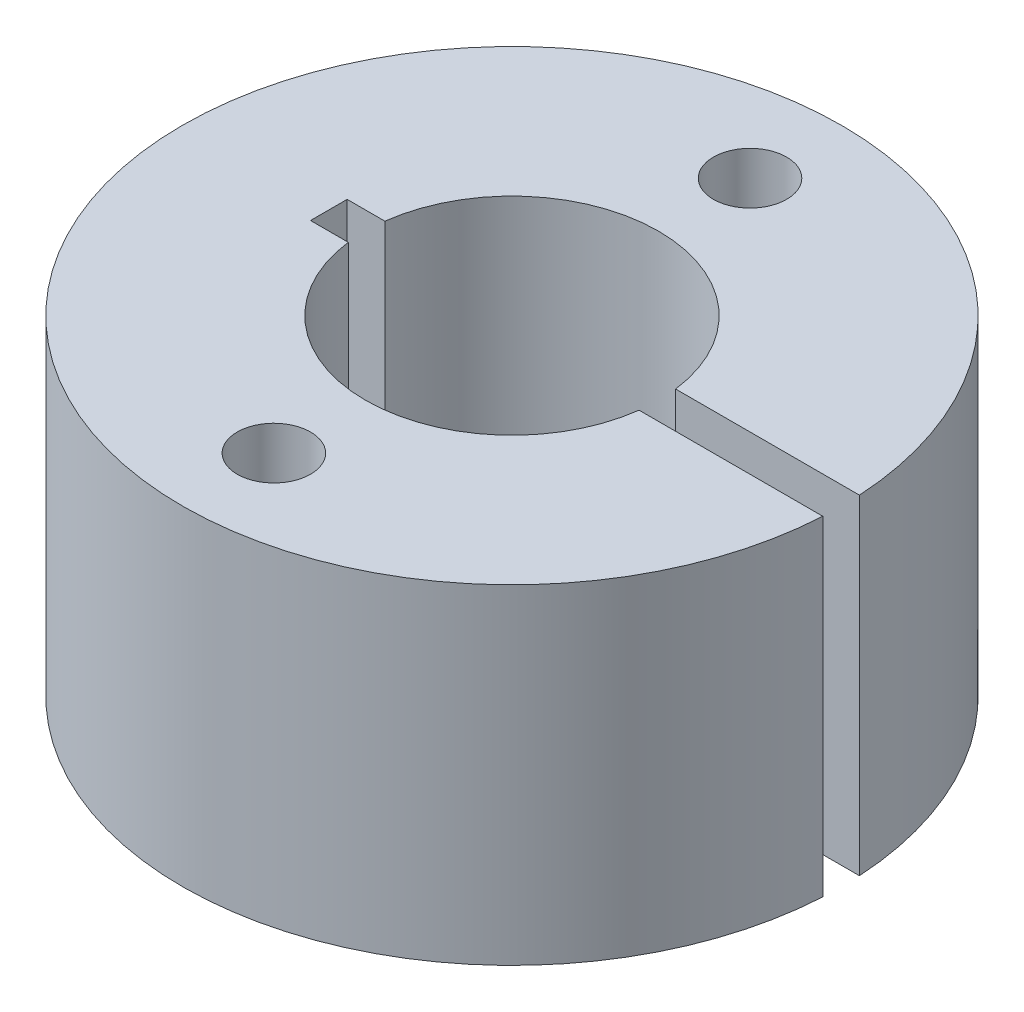
SolidWorks part; units mm, degrees
ref_plane "Plan de face" through (0, 0, 0) normal (0, 0, 1) x (1, 0, 0)
ref_plane "Plan de dessus" through (0, 0, 0) normal (0, 1, 0) x (1, 0, 0)
ref_plane "Plan de droite" through (0, 0, 0) normal (1, 0, 0) x (0, 0, -1)
sketch "Esquisse1" plane through (0, 0, 0) normal (0, 1, 0) x (1, 0, 0)
  line L0 (3.9686, 0.5) -> (8.9861, 0.5)
  line L1 (-5, 0.5) -> (-3.9686, 0.5)
  line L2 (-5, 0.5) -> (-5, -0.5)
  line L3 (-5, -0.5) -> (-3.9686, -0.5)
  line L4 (3.9686, -0.5) -> (8.9861, -0.5)
  arc A0 (8.9861, 0.5) -> (8.9861, -0.5) centre (0, 0) ccw
  arc A1 (3.9686, 0.5) -> (-3.9686, 0.5) centre (0, 0) ccw
  arc A2 (-3.9686, -0.5) -> (3.9686, -0.5) centre (0, 0) ccw
  point P8 (-5, 0)
  dimension "D1" = 18
  dimension "D2" = 8
  dimension "D3" = 5
  dimension "D4" = 1
extrude "Boss.-Extru.1" add sketch "Esquisse1" along normal blind 9
sketch "Esquisse2" plane through (0, 9, 0) normal (0, 1, 0) x (1, 0, 0)
  line L0 (0, 6.5) -> (0, -6.5) construction
  circle A0 centre (0, -6.5) radius 1
  circle A1 centre (0, 6.5) radius 1
  dimension "D1" = 2
  dimension "D2" = 13
extrude "Enlèv. mat.-Extru.1" cut sketch "Esquisse2" against normal through all
